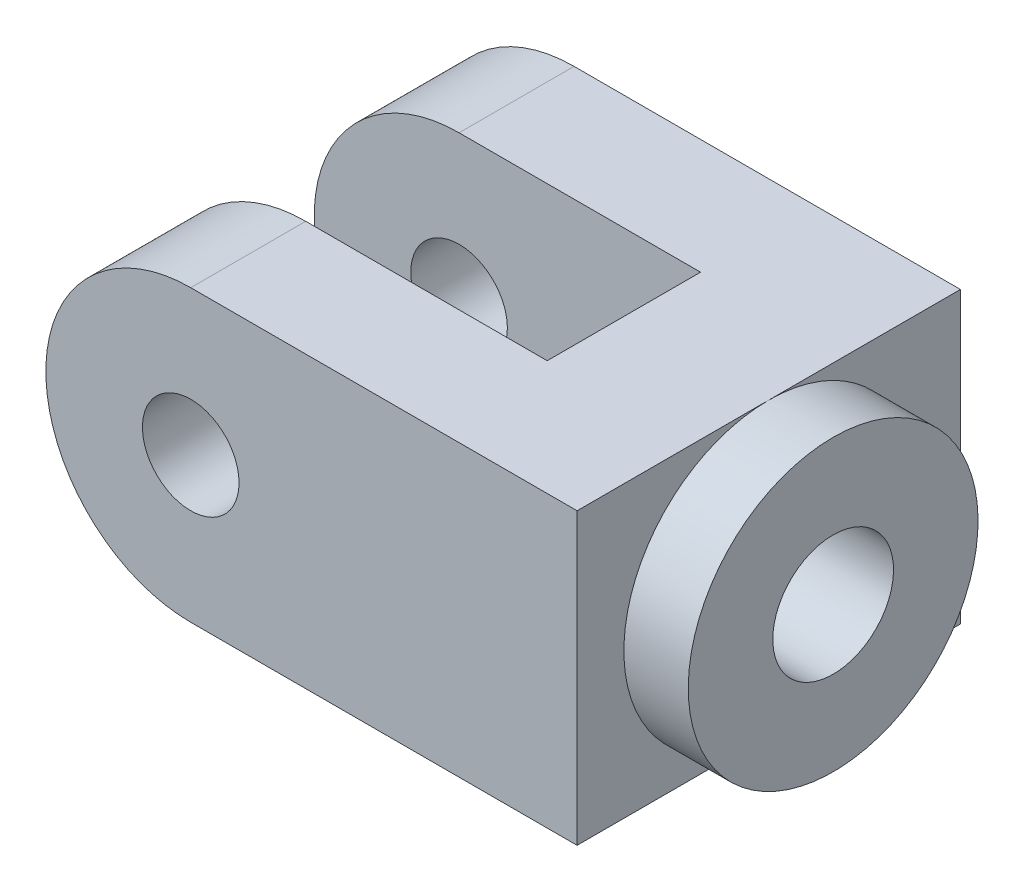
SolidWorks part; units mm, degrees
ref_plane "Front Plane" through (0, 0, 0) normal (0, 0, 1) x (1, 0, 0)
ref_plane "Top Plane" through (0, 0, 0) normal (0, 1, 0) x (1, 0, 0)
ref_plane "Right Plane" through (0, 0, 0) normal (1, 0, 0) x (0, 0, -1)
sketch "Sketch1" plane through (0, 0, 0) normal (0, 0, 1) x (1, 0, 0)
  line L1 (-66, 36) -> (66, 36)
  line L2 (-66, 36) -> (-66, -36)
  line L3 (-66, -36) -> (66, -36)
  line L4 (66, 36) -> (66, -36)
  line L5 (-66, 36) -> (66, -36) construction
  line L6 (-66, -36) -> (66, 36) construction
  point P0 (0, 0)
  dimension "D1" = 132
  dimension "D2" = 72
extrude "Boss-Extrude1" add sketch "Sketch1" along normal mid plane 95.25
sketch "Sketch2" plane through (0, 0, 47.625) normal (0, 0, 1) x (1, 0, 0)
  line L0 (66, 36) -> (-66, 36) construction
  line L1 (-66, -36) -> (66, -36) construction
  line L2 (-66, 36) -> (-66, -36) construction
  arc A0 (-30, 36) -> (-30, -36) centre (-30, 0) ccw
  dimension "D1" = 36
extrude "Cut-Extrude1" cut sketch "Sketch2" against normal through all and the other way through all flip side to cut
sketch "Sketch3" plane through (0, 36, 0) normal (0, 1, 0) x (1, 0, 0)
  line L0 (-66, 47.625) -> (-66, -47.625) construction
  line L1 (30, 19.05) -> (-66, 19.05)
  line L2 (30, 19.05) -> (30, -19.05)
  line L3 (30, -19.05) -> (-66, -19.05)
  line L4 (-66, 19.05) -> (-66, -19.05)
  line L5 (66, -47.625) -> (-30, -47.625) construction
  line L6 (-30, -47.625) -> (-30, 47.625) construction
  dimension "D1" = 38.1
  dimension "D2" = 28.575
  dimension "D3" = 60
extrude "Cut-Extrude2" cut sketch "Sketch3" against normal blind 85.25
sketch "Sketch4" plane through (66, 0, 0) normal (1, 0, 0) x (0, 0, -1)
  circle A0 centre (0, 0) radius 15
  dimension "D1" = 30
extrude "Cut-Extrude3" cut sketch "Sketch4" against normal blind 85.25
sketch "Sketch5" plane through (66, 0, 0) normal (1, 0, 0) x (0, 0, -1)
  circle A0 centre (0, 0) radius 36
  circle A1 centre (0, 0) radius 15 construction
  circle A2 centre (0, 0) radius 15
  dimension "D1" = 72
extrude "Boss-Extrude2" add sketch "Sketch5" along normal blind 16
sketch "Sketch6" plane through (0, 0, 47.625) normal (0, 0, 1) x (1, 0, 0)
  circle A0 centre (-30, 0) radius 12
  arc A1 (-30, 36) -> (-30, -36) centre (-30, 0) ccw construction
  dimension "D1" = 24
extrude "Cut-Extrude4" cut sketch "Sketch6" against normal through all and the other way through all
scale "Scale1" scale about centroid uniform scaling yes scale factor 0.53
scale "Scale2" scale about centroid uniform scaling yes scale factor 0.66
